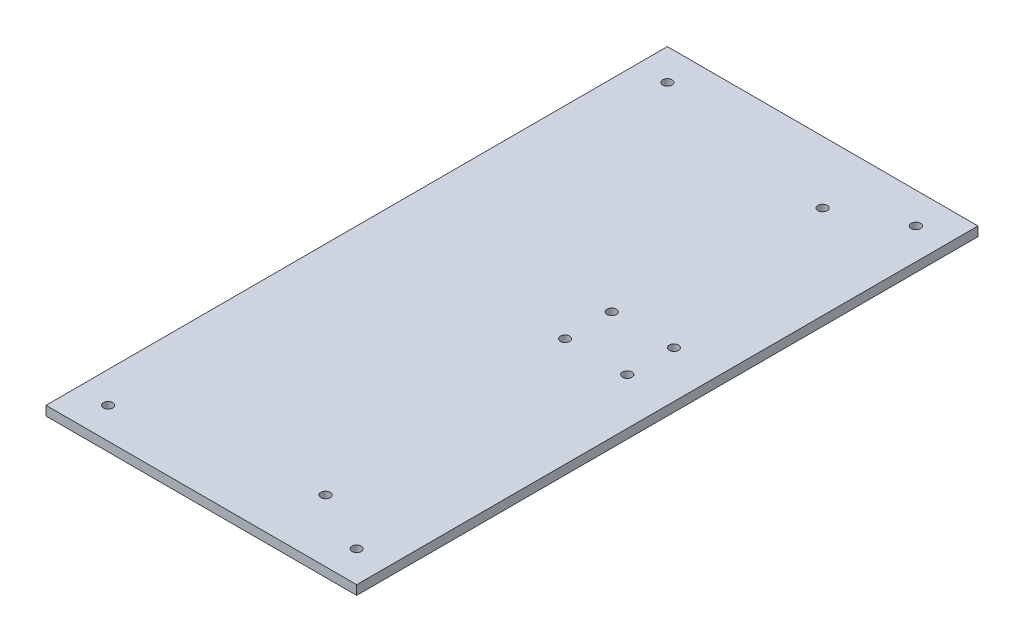
SolidWorks part; units mm, degrees
material "Acrylic (Medium-high impact)"
ref_plane "Front Plane" through (0, 0, 0) normal (0, 0, 1) x (1, 0, 0)
ref_plane "Top Plane" through (0, 0, 0) normal (0, 1, 0) x (1, 0, 0)
ref_plane "Right Plane" through (0, 0, 0) normal (1, 0, 0) x (0, 0, -1)
sketch "Sketch1" plane through (0, 0, 0) normal (0, 1, 0) x (1, 0, 0)
  line L1 (50, -100) -> (-50, -100)
  line L2 (50, -100) -> (50, 100)
  line L3 (50, 100) -> (-50, 100)
  line L4 (-50, -100) -> (-50, 100)
  line L5 (50, -100) -> (-50, 100) construction
  line L6 (50, 100) -> (-50, -100) construction
  point P0 (0, 0)
  dimension "D1" = 100
  dimension "D2" = 200
extrude "Boss-Extrude1" add sketch "Sketch1" along normal blind 3
sketch "Sketch2" plane through (0, 3, 0) normal (0, 1, 0) x (1, 0, 0)
  line L0 (-50, 100) -> (-50, -100) construction
  line L2 (-50, -100) -> (50, -100) construction
  line L3 (0, -100) -> (0, 100) construction
  line L4 (50, 100) -> (-50, 100) construction
  line L5 (50, 0) -> (-50, 0) construction
  line L6 (50, -100) -> (50, 100) construction
  circle A0 centre (-40, -90) radius 1.5
  circle A1 centre (40, -90) radius 1.5
  circle A2 centre (40, 90) radius 1.5
  circle A3 centre (-40, 90) radius 1.5
  dimension "D1" = 3
  dimension "D2" = 10
  dimension "D3" = 10
extrude "Cut-Extrude1" cut sketch "Sketch2" against normal blind 3
sketch "Sketch3" plane through (0, 3, 0) normal (0, 1, 0) x (1, 0, 0)
  line L0 (50, -100) -> (50, 100) construction
  line L1 (50, 100) -> (-50, 100) construction
  line L2 (50, 0) -> (-50, 0) construction
  line L3 (-50, 100) -> (-50, -100) construction
  circle A0 centre (20, 80) radius 1.5
  circle A1 centre (20, -80) radius 1.5
  dimension "D1" = 3
  dimension "D2" = 30
  dimension "D3" = 20
extrude "Cut-Extrude2" cut sketch "Sketch3" against normal blind 25
sketch "Sketch4" plane through (0, 3, 0) normal (0, 1, 0) x (1, 0, 0)
  line L0 (50, 0) -> (-50, 0) construction
  line L1 (50, -100) -> (50, 100) construction
  line L2 (-50, 100) -> (-50, -100) construction
  circle A0 centre (35, 17.1) radius 1.5
  circle A1 centre (15, 2.1) radius 1.5
  circle A2 centre (15, 17.1) radius 1.5
  circle A3 centre (35, 2.1) radius 1.5
  dimension "D1" = 3
  dimension "D4" = 3
  dimension "D7" = 3
  dimension "D10" = 3
  dimension "D2" = 15
  dimension "D3" = 17.1
  dimension "D5" = 20
  dimension "D6" = 17.1
  dimension "D8" = 15
  dimension "D9" = 20
  dimension "D11" = 20
  dimension "D12" = 15
extrude "Cut-Extrude3" cut sketch "Sketch4" against normal blind 3
